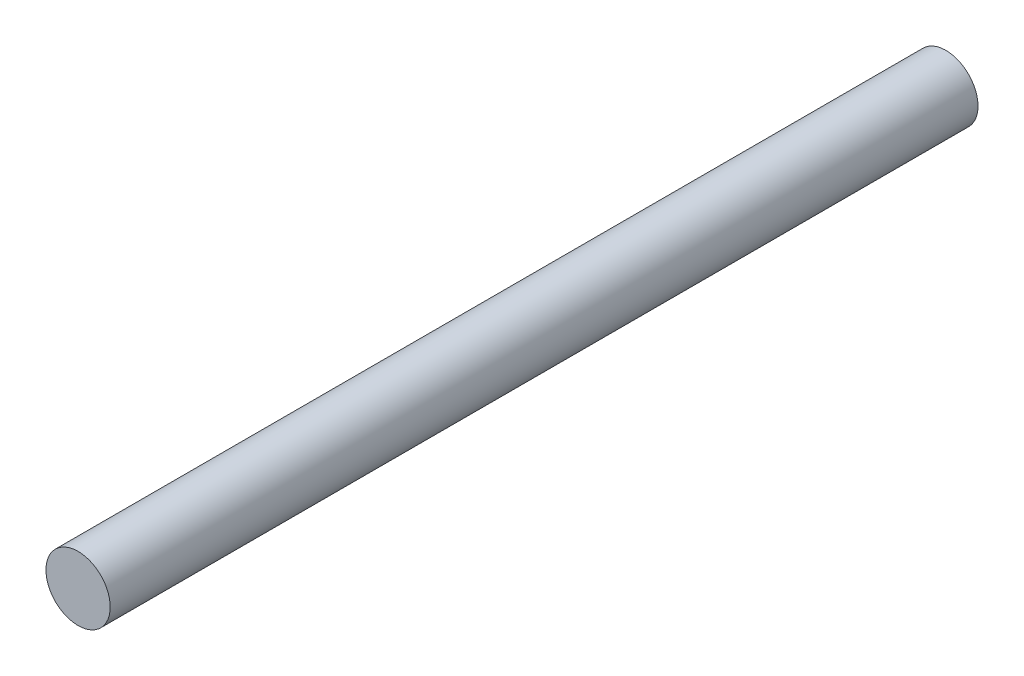
SolidWorks part; units mm, degrees
ref_plane "前视基准面" through (0, 0, 0) normal (0, 0, 1) x (1, 0, 0)
ref_plane "上视基准面" through (0, 0, 0) normal (0, 1, 0) x (1, 0, 0)
ref_plane "右视基准面" through (0, 0, 0) normal (1, 0, 0) x (0, 0, -1)
sketch "草图1" plane through (0, 0, 0) normal (0, 0, 1) x (1, 0, 0)
  circle A0 centre (0, 0) radius 5
  dimension "D1" = 10
extrude "凸台-拉伸1" add sketch "草图1" along normal blind 135
cosmetic thread "装饰螺纹线1" parameters "D1"=150, "D2"=8.376
